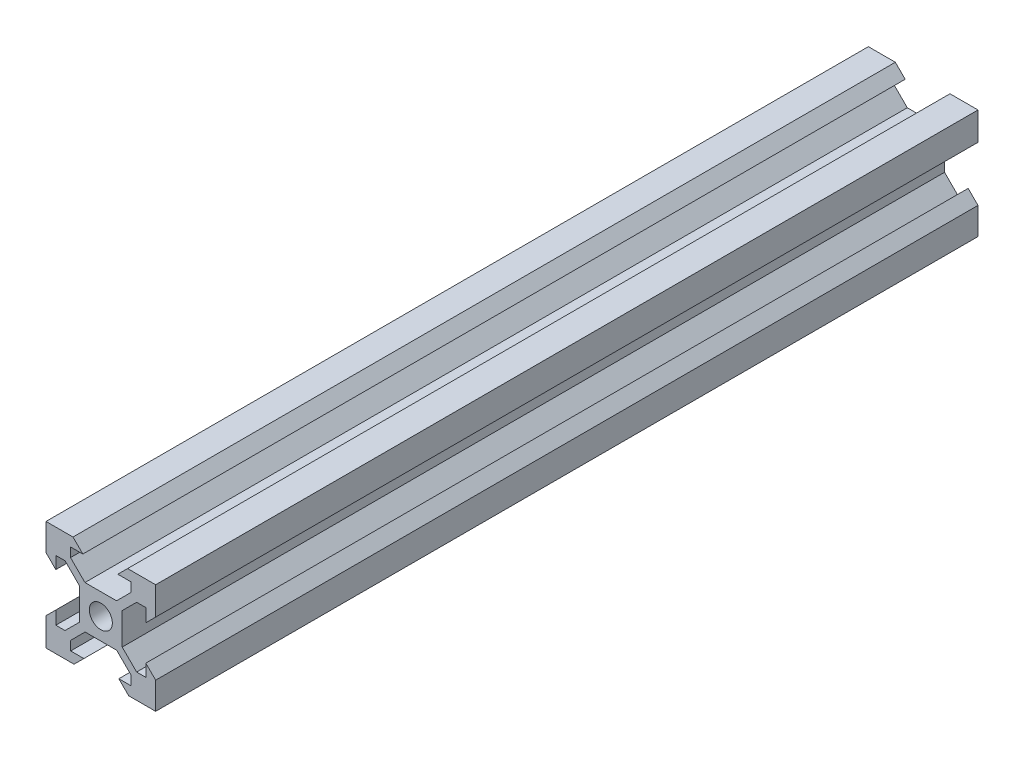
SolidWorks part; units mm, degrees
ref_plane "Front Plane" through (0, 0, 0) normal (0, 0, 1) x (1, 0, 0)
ref_plane "Top Plane" through (0, 0, 0) normal (0, 1, 0) x (1, 0, 0)
ref_plane "Right Plane" through (0, 0, 0) normal (1, 0, 0) x (0, 0, -1)
sketch "Sketch1"
  line L0 (3.6782, 7.2976) -> (17.6348, 7.2976) construction
  line L1 (0, 0) -> (59.361, 0) construction
  line L6 (-10, -10) -> (10, 10) construction
  line L7 (-10, 10) -> (10, -10) construction
  line L8 (-10, 10) -> (10, -10) construction
  line L9 (-10, -10) -> (10, 10) construction
  line L10 (-5.0746, 10) -> (-3.2822, 8.2076)
  line L11 (-3.2822, 8.2076) -> (-5.5259, 8.2076)
  line L12 (-5.5259, 8.2076) -> (-5.5259, 6.528)
  line L13 (-5.5259, 6.528) -> (-2.8971, 3.8992)
  line L14 (-2.8971, 3.8992) -> (2.8681, 3.8992)
  line L15 (2.8681, 3.8992) -> (5.4968, 6.528)
  line L16 (5.4968, 6.528) -> (5.4968, 8.2076)
  line L17 (5.4968, 8.2076) -> (3.0937, 8.2076)
  line L18 (3.0937, 8.2076) -> (4.8861, 10)
  line L19 (-10, 5.0746) -> (-10, 10)
  line L20 (-10, 10) -> (-5.0746, 10)
  line L21 (-6.528, -5.4968) -> (-8.2076, -5.4968)
  line L22 (-8.2076, -3.0937) -> (-10, -4.8861)
  line L23 (-8.2076, -5.4968) -> (-8.2076, -3.0937)
  line L24 (-6.528, 5.5259) -> (-3.8992, 2.8971)
  line L25 (-3.8992, -2.8681) -> (-6.528, -5.4968)
  line L26 (-3.8992, 2.8971) -> (-3.8992, -2.8681)
  line L28 (10, -10) -> (5.0746, -10)
  line L30 (-10, -4.8861) -> (-10, -10)
  line L31 (-8.2076, 5.5259) -> (-6.528, 5.5259)
  line L32 (-8.2076, 3.2822) -> (-8.2076, 5.5259)
  line L33 (-10, 5.0746) -> (-8.2076, 3.2822)
  line L34 (5.0746, -10) -> (3.2822, -8.2076)
  line L35 (3.2822, -8.2076) -> (5.5259, -8.2076)
  line L36 (5.5259, -8.2076) -> (5.5259, -6.528)
  line L37 (2.8971, -3.8992) -> (-2.8681, -3.8992)
  line L38 (-2.8681, -3.8992) -> (-5.4968, -6.528)
  line L39 (5.5259, -6.528) -> (2.8971, -3.8992)
  line L40 (-5.4968, -8.2076) -> (-3.0937, -8.2076)
  line L41 (-3.0937, -8.2076) -> (-4.8861, -10)
  line L42 (-5.4968, -6.528) -> (-5.4968, -8.2076)
  line L43 (-10, -10) -> (-4.8861, -10)
  line L44 (8.2076, 3.0937) -> (10, 4.8861)
  line L45 (8.2076, 5.4968) -> (8.2076, 3.0937)
  line L46 (6.528, 5.4968) -> (8.2076, 5.4968)
  line L47 (3.8992, 2.8681) -> (6.528, 5.4968)
  line L48 (3.8992, -2.8971) -> (3.8992, 2.8681)
  line L49 (6.528, -5.5259) -> (3.8992, -2.8971)
  line L50 (8.2076, -5.5259) -> (6.528, -5.5259)
  line L51 (8.2076, -3.2822) -> (8.2076, -5.5259)
  line L52 (10, -5.0746) -> (8.2076, -3.2822)
  line L53 (5.0746, -10) -> (10, -10)
  line L54 (10, 4.8861) -> (10, 10)
  line L56 (10, 10) -> (4.8861, 10)
  line L57 (5.0746, -10) -> (10, -10)
  line L60 (10, -10) -> (10, -5.0746)
  circle A0 centre (0, 0) radius 2.1
  point P2 (0, 0)
other "Pen Sketch1" parameters "D3"=2.0969, "D1"=797.2567, "D2"=2.8793
extrude "Boss-Extrude1" add sketch "Sketch1" along normal blind 150
